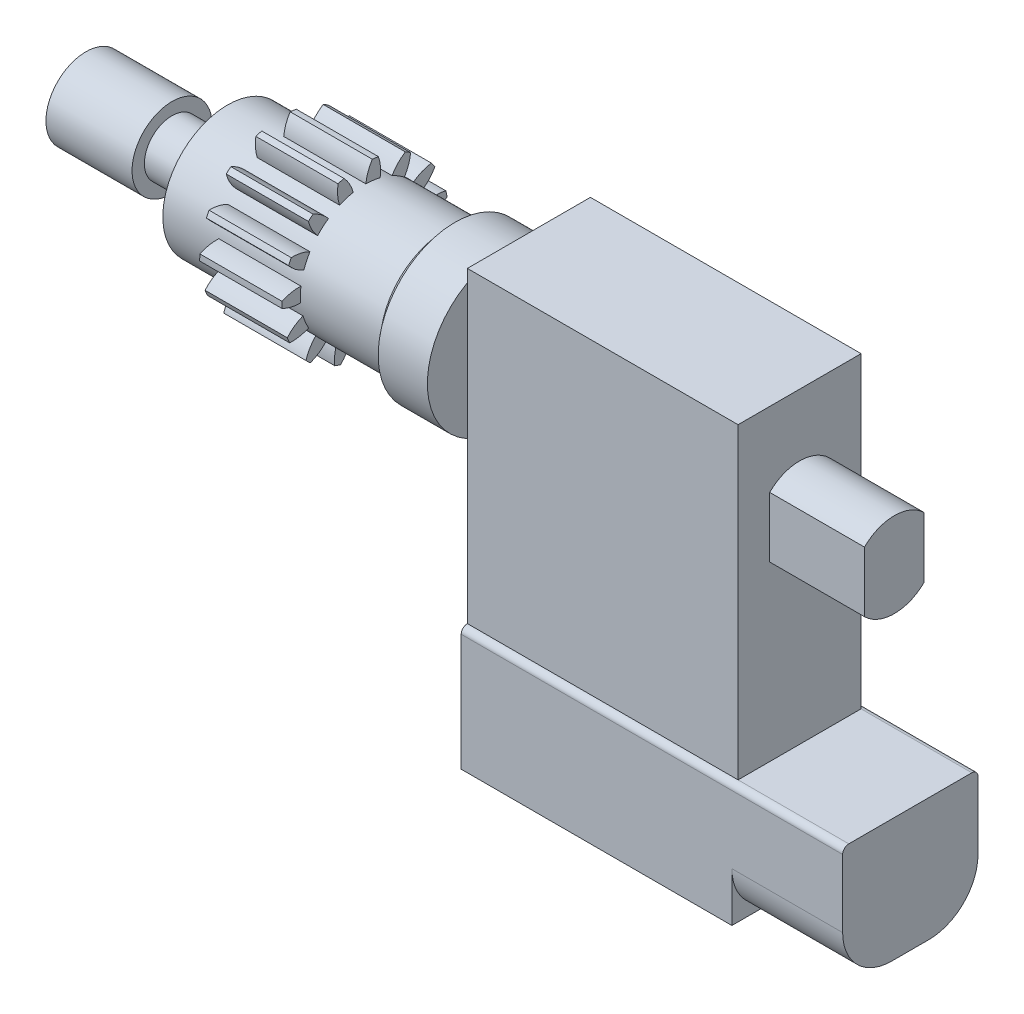
SolidWorks part; units mm, degrees
ref_plane "Plan de face" through (0, 0, 0) normal (0, 0, 1) x (1, 0, 0)
ref_plane "Plan de dessus" through (0, 0, 0) normal (0, 1, 0) x (1, 0, 0)
ref_plane "Plan de droite" through (0, 0, 0) normal (1, 0, 0) x (0, 0, -1)
sketch "Esquisse1" plane through (0, 0, 0) normal (0, 0, 1) x (1, 0, 0)
  line L1 (0, 0) -> (22, 0)
  line L2 (0, 0) -> (0, 25)
  line L3 (0, 25) -> (22, 25)
  line L4 (22, 0) -> (22, 25)
  dimension "D1" = 25
  dimension "D2" = 22
extrude "Extrusion1" add sketch "Esquisse1" along normal mid plane 10
sketch "Esquisse2" plane through (0, 0, 0) normal (-1, 0, 0) x (0, 0, 1)
  line L0 (5, 25) -> (-5, 25) construction
  line L1 (-5, 0) -> (5, 0)
  line L2 (-5.5, -0.5) -> (-5.5, -10)
  line L3 (-5.5, -10) -> (5.5, -10)
  line L4 (5.5, -0.5) -> (5.5, -10)
  line L5 (5, 0) -> (-5, 0) construction
  line L6 (0, 25) -> (0, -17.3851) construction
  arc A0 (-5, 0) -> (-5.5, -0.5) centre (-5, -0.5) ccw
  arc A1 (5, 0) -> (5.5, -0.5) centre (5, -0.5) cw
  dimension "D3" = 0.5
  dimension "D4" = 0.5
  dimension "D1" = 35
  dimension "D2" = 11
extrude "Extrusion2" add sketch "Esquisse2" against normal up to surface (22 mm away) up to face at (22, 12.5, 0)
sketch "Esquisse4" plane through (22, 0, 0) normal (1, 0, 0) x (0, 0, -1)
  line L0 (5.5, -10) -> (5.5, -0.5) construction
  line L1 (-5.5, -0.5) -> (-5.5, -10) construction
  line L2 (5.5, -6) -> (5.5, -0.5)
  line L3 (-5.5, -0.5) -> (-5.5, -6)
  line L4 (-5, 0) -> (5, 0)
  line L5 (-1.5, -10) -> (1.5, -10)
  arc A0 (5.5, -0.5) -> (5, 0) centre (5, -0.5) ccw construction
  arc A1 (-5, 0) -> (-5.5, -0.5) centre (-5, -0.5) ccw construction
  arc A2 (5.5, -0.5) -> (5, 0) centre (5, -0.5) ccw
  arc A3 (-5, 0) -> (-5.5, -0.5) centre (-5, -0.5) ccw
  arc A4 (-5.5, -6) -> (-1.5, -10) centre (-1.5, -6) ccw
  arc A5 (5.5, -6) -> (1.5, -10) centre (1.5, -6) cw
  dimension "D1" = 4
extrude "Extrusion3" add sketch "Esquisse4" along normal blind 9
sketch "Esquisse5" plane through (22, 0, 0) normal (1, 0, 0) x (0, 0, -1)
  line L0 (-5, 25) -> (5, 25) construction
  line L2 (0, 25) -> (0, 0) construction
  line L4 (-2.429, 18.95) -> (-2.429, 14.05)
  line L6 (2.429, 18.95) -> (2.429, 14.05)
  arc A0 (-2.429, 14.05) -> (2.429, 14.05) centre (0, 16.5) ccw
  arc A1 (2.429, 18.95) -> (-2.429, 18.95) centre (0, 16.5) ccw
  dimension "D3" = 6.9
  dimension "D1" = 8.5
  dimension "D4" = 4.9
extrude "Extrusion4" add sketch "Esquisse5" along normal blind 7.7
sketch "Esquisse6" plane through (0, 0, 0) normal (-1, 0, 0) x (0, 0, 1)
  circle A0 centre (0, 16.5) radius 1.25
  arc A1 (2.429, 18.95) -> (-2.429, 18.95) centre (0, 16.5) ccw construction
  dimension "D3" = 2.5
extrude "Extrusion5" add sketch "Esquisse6" along normal blind 36
ref_plane "Plan2" through (0, 0, 10.1) normal (0, 0, 1) x (1, 0, 0)
ref_axis "Axe1" through (0, 16.5, 0) along (-1, 0, 0)
sketch "Esquisse7" plane through (0, 0, 0) normal (0, 0, 1) x (1, 0, 0)
  line L0 (-2, 17.75) -> (-2, 22.75)
  line L1 (-2, 22.75) -> (-6, 22.75)
  line L2 (-6, 22.75) -> (-6.8215, 21.75)
  line L3 (-6.8215, 21.75) -> (-13.3215, 21.75)
  line L4 (-13.3215, 21.75) -> (-13.3215, 23.25)
  line L5 (-13.3215, 23.25) -> (-20, 23.25)
  line L6 (-20, 23.25) -> (-20, 21.75)
  line L7 (-20, 21.75) -> (-24.5, 21.75)
  line L8 (-24.5, 21.75) -> (-24.5, 18.75)
  line L9 (-24.5, 18.75) -> (-29, 18.75)
  line L10 (-29, 18.75) -> (-29, 19.75)
  line L11 (-29, 19.75) -> (-36, 19.75)
  line L12 (-36, 19.75) -> (-36, 17.75)
  line L13 (-36, 17.75) -> (-36, 15.25) construction
  line L14 (-36, 17.75) -> (-2, 17.75)
  line L15 (0, 25) -> (0, 0) construction
  line L16 (0, 17.75) -> (-36, 17.75) construction
  dimension "D1" = 4
  dimension "D2" = 7
  dimension "D3" = 4.5
  dimension "D4" = 4.5
  dimension "D5" = 6.5
  dimension "D6" = 2
  dimension "D7" = 5
  dimension "D8" = 4
  dimension "D9" = 2
  dimension "D10" = 1
  dimension "D11" = 4
  dimension "D12" = 5.5
revolve "Révolution1" add sketch "Esquisse7" angle 360 about axis through (0, 16.5, 0) along (-1, 0, 0)
sketch "Esquisse8" plane through (-20, 0, 0) normal (-1, 0, 0) x (0, 0, 1)
  line L0 (2.4565, 24.6373) -> (0, 16.5) construction
  line L15 (2.4565, 24.6373) -> (0, 16.5) construction
  arc A0 (2.1881, 22.8855) -> (2.067, 21.326) centre (-1.0574, 22.3529) cw
  circle A1 centre (0, 16.5) radius 5.25 construction
  circle A2 centre (0, 16.5) radius 6.75 construction
  arc A3 (1.7107, 23.0296) -> (0.9486, 21.6636) centre (4.1194, 20.7901) ccw
  arc A4 (0.9486, 21.6636) -> (-0.0746, 21.7495) centre (0, 16.5) ccw
  arc A5 (2.1881, 22.8855) -> (1.7107, 23.0296) centre (0, 16.5) ccw
  arc A6 (-0.5983, 23.2234) -> (-1.093, 23.1609) centre (0, 16.5) ccw
  arc A7 (-0.5983, 23.2234) -> (-0.0746, 21.7495) centre (-3.3466, 21.4168) cw
  arc A8 (-1.093, 23.1609) -> (-1.2336, 21.603) centre (2.0183, 22.0948) ccw
  arc A9 (-3.2812, 22.3988) -> (-3.7078, 22.1405) centre (0, 16.5) ccw
  arc A10 (-3.2812, 22.3988) -> (-2.2033, 21.2653) centre (-5.0571, 19.6306) cw
  arc A11 (-3.7078, 22.1405) -> (-3.2026, 20.6601) centre (-0.4318, 22.432) ccw
  arc A12 (-5.3968, 20.5542) -> (-5.6814, 20.1448) centre (0, 16.5) ccw
  arc A13 (-5.3968, 20.5542) -> (-3.951, 19.9572) centre (-5.8932, 17.303) cw
  arc A14 (-5.6814, 20.1448) -> (-4.6177, 18.9978) centre (-2.8072, 21.7435) ccw
  arc A15 (-6.5792, 18.0086) -> (-6.6727, 17.5188) centre (0, 16.5) ccw
  arc A16 (-6.5792, 18.0086) -> (-5.0156, 18.0513) centre (-5.7103, 14.8366) cw
  arc A17 (-6.6727, 17.5188) -> (-5.2345, 16.9037) centre (-4.6972, 20.1484) ccw
  arc A18 (-6.6241, 15.2022) -> (-6.5102, 14.7167) centre (0, 16.5) ccw
  arc A19 (-6.6241, 15.2022) -> (-5.2129, 15.8771) centre (-4.5401, 12.6578) cw
  arc A20 (-6.5102, 14.7167) -> (-4.9461, 14.7397) centre (-5.7751, 17.9224) ccw
  arc A21 (-5.5235, 12.6201) -> (-5.222, 12.223) centre (0, 16.5) ccw
  arc A22 (-5.5235, 12.6201) -> (-4.5089, 13.8107) centre (-2.5848, 11.1433) cw
  arc A23 (-5.222, 12.223) -> (-3.8025, 12.8801) centre (-5.8544, 15.4505) ccw
  arc A24 (-3.4679, 10.709) -> (-3.0309, 10.4688) centre (0, 16.5) ccw
  arc A25 (-3.4679, 10.709) -> (-3.0252, 12.2093) centre (-0.1826, 10.5551) cw
  arc A26 (-3.0309, 10.4688) -> (-2.0014, 11.6465) centre (-4.9214, 13.1601) ccw
  arc A27 (-0.8127, 9.7991) -> (-0.3158, 9.7574) centre (0, 16.5) ccw
  arc A28 (-0.8127, 9.7991) -> (-1.0185, 11.3497) centre (2.2512, 10.9948) cw
  arc A29 (-0.3158, 9.7574) -> (0.1457, 11.252) centre (-3.1374, 11.4471) ccw
  arc A30 (1.9831, 10.0479) -> (2.454, 10.2119) centre (0, 16.5) ccw
  arc A31 (1.9831, 10.0479) -> (1.1643, 11.3807) centre (4.2957, 12.3864) cw
  arc A32 (2.454, 10.2119) -> (2.2677, 11.765) centre (-0.811, 10.6079) ccw
  arc A33 (4.436, 11.4123) -> (4.7995, 11.7537) centre (0, 16.5) ccw
  arc A34 (4.436, 11.4123) -> (3.1459, 12.2969) centre (5.5975, 14.4893) cw
  arc A35 (4.7995, 11.7537) -> (3.9975, 13.0967) centre (1.6557, 10.7874) ccw
  arc A36 (6.1218, 13.6564) -> (6.315, 14.1161) centre (0, 16.5) ccw
  arc A37 (6.1218, 13.6564) -> (4.5835, 13.9398) centre (5.9314, 16.9398) cw
  arc A38 (6.315, 14.1161) -> (5.0361, 15.0169) centre (3.8361, 11.9547) ccw
  arc A39 (6.7491, 16.3922) -> (6.7387, 16.8908) centre (0, 16.5) ccw
  arc A40 (6.7491, 16.3922) -> (5.2285, 16.0254) centre (5.2397, 19.3143) cw
  arc A41 (6.7387, 16.8908) -> (5.204, 17.1935) centre (5.3531, 13.9079) ccw
  arc A42 (6.2095, 19.1467) -> (5.9972, 19.5978) centre (0, 16.5) ccw
  arc A43 (6.2095, 19.1467) -> (4.9695, 18.1931) centre (3.642, 21.2022) cw
  arc A44 (5.9972, 19.5978) -> (4.472, 19.2502) centre (5.9446, 16.3094) ccw
  arc A45 (4.5961, 21.4435) -> (4.2187, 21.7693) centre (0, 16.5) ccw
  arc A46 (4.5961, 21.4435) -> (3.8512, 20.068) centre (1.4146, 22.277) cw
  arc A47 (4.2187, 21.7693) -> (2.9668, 20.8313) centre (5.5082, 18.7437) ccw
  arc A48 (2.1881, 22.8855) -> (1.7107, 23.0296) centre (0, 16.5) ccw
  arc A49 (2.1881, 22.8855) -> (2.067, 21.326) centre (-1.0574, 22.3529) cw
  arc A50 (1.7107, 23.0296) -> (0.9486, 21.6636) centre (4.1194, 20.7901) ccw
  arc A51 (2.9668, 20.8313) -> (2.067, 21.326) centre (0, 16.5) ccw
  arc A52 (4.472, 19.2502) -> (3.8512, 20.068) centre (0, 16.5) ccw
  arc A53 (5.204, 17.1935) -> (4.9695, 18.1931) centre (0, 16.5) ccw
  arc A54 (5.0361, 15.0169) -> (5.2285, 16.0254) centre (0, 16.5) ccw
  arc A55 (3.9975, 13.0967) -> (4.5835, 13.9398) centre (0, 16.5) ccw
  arc A56 (-3.8025, 12.8801) -> (-3.0252, 12.2093) centre (0, 16.5) ccw
  arc A57 (-4.9461, 14.7397) -> (-4.5089, 13.8107) centre (0, 16.5) ccw
  arc A58 (-5.2345, 16.9037) -> (-5.2129, 15.8771) centre (0, 16.5) ccw
  arc A59 (-4.6177, 18.9978) -> (-5.0156, 18.0513) centre (0, 16.5) ccw
  arc A60 (-3.2026, 20.6601) -> (-3.951, 19.9572) centre (0, 16.5) ccw
  arc A61 (-1.2336, 21.603) -> (-2.2033, 21.2653) centre (0, 16.5) ccw
  arc A62 (-2.0014, 11.6465) -> (-1.0185, 11.3497) centre (0, 16.5) ccw
  arc A63 (0.1457, 11.252) -> (1.1643, 11.3807) centre (0, 16.5) ccw
  arc A64 (2.2677, 11.765) -> (3.1459, 12.2969) centre (0, 16.5) ccw
  circle M1 centre (0, 16.5) radius 5.25
  circle M2 centre (0, 16.5) radius 6.75
extrude "Enlèv. mat.-Extru.2" cut sketch "Esquisse8" against normal up to surface (6.6785 mm away) contours A13 A11 M2 M1 | A10 A8 M2 M1 | A7 A3 M2 M1 | A47 A0 M2 M1 | A46 A44 M2 M1 | A43 A41 M2 M1 | A40 A38 M2 M1 | A37 A35 M2 M1 | A34 A32 M2 M1 | A16 A14 M2 M1 | A19 A17 M2 M1 | A22 A20 M2 M1 | A28 A26 M2 M1 | A31 A29 M2 M1 | A25 A23 M2 M1 up to face at (-13.3215, 16.5, -6.75)
